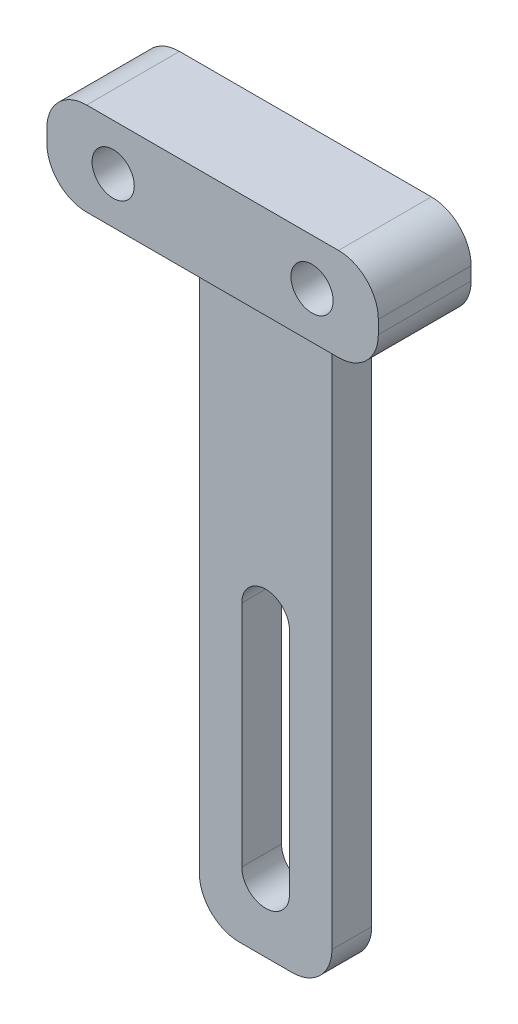
SolidWorks part; units mm, degrees
ref_plane "Front Plane" through (0, 0, 0) normal (0, 0, 1) x (1, 0, 0)
ref_plane "Top Plane" through (0, 0, 0) normal (0, 1, 0) x (1, 0, 0)
ref_plane "Right Plane" through (0, 0, 0) normal (1, 0, 0) x (0, 0, -1)
sketch "Sketch1" plane through (0, 0, 0) normal (0, 0, 1) x (1, 0, 0)
  line L0 (-12.5497, 17.2378) -> (-5.0497, 17.2378)
  line L1 (-30.0497, 24.2378) -> (-5.0497, 24.2378)
  line L2 (-30.0497, 24.2378) -> (-30.0497, 17.2378)
  line L3 (-30.0497, 17.2378) -> (-22.5497, 17.2378)
  line L4 (-5.0497, 24.2378) -> (-5.0497, 17.2378)
  line L5 (-30.0497, 24.2378) -> (-5.0497, 17.2378) construction
  line L6 (-30.0497, 17.2378) -> (-5.0497, 24.2378) construction
  line L7 (-17.5497, -23.6845) -> (-17.5497, -6.4384) construction
  line L8 (-19.3497, -23.6845) -> (-19.3497, -6.4384)
  line L9 (-22.5497, 17.2378) -> (-22.5497, -28.6845)
  line L10 (-22.5497, -28.6845) -> (-12.5497, -28.6845)
  line L11 (-12.5497, 17.2378) -> (-12.5497, -28.6845)
  line L12 (-15.7497, -23.6845) -> (-15.7497, -6.4384)
  arc A0 (-19.3497, -23.6845) -> (-15.7497, -23.6845) centre (-17.5497, -23.6845) ccw
  arc A1 (-15.7497, -6.4384) -> (-19.3497, -6.4384) centre (-17.5497, -6.4384) ccw
  point P0 (-17.5497, 20.7378)
  point P11 (-17.5497, -15.0614)
  dimension "D3" = 1.8
  dimension "D1" = 25
  dimension "D2" = 7
  dimension "D4" = 5
extrude "Boss-Extrude1" add sketch "Sketch1" along normal blind 3
sketch "Sketch3" plane through (0, 0, 3) normal (0, 0, 1) x (1, 0, 0)
  line L1 (-30.0497, 24.2378) -> (-5.0497, 24.2378)
  line L2 (-30.0497, 24.2378) -> (-30.0497, 17.2378)
  line L3 (-30.0497, 17.2378) -> (-5.0497, 17.2378)
  line L4 (-5.0497, 24.2378) -> (-5.0497, 17.2378)
extrude "Boss-Extrude2" add sketch "Sketch3" along normal blind 4 contours L3 L4 L1 L2
sketch "Sketch2" plane through (0, 0, 0) normal (0, 0, 1) x (1, 0, 0)
  line L0 (-17.5497, 24.2378) -> (-17.5497, -44.1864) construction
  line L2 (-5.0497, 24.2378) -> (-30.0497, 24.2378) construction
  circle A0 centre (-25.0497, 20.7378) radius 1.5923
  circle A1 centre (-10.0497, 20.7378) radius 1.5923
  dimension "D1" = 15
  dimension "D2" = 7.5
  dimension "D3" = 3.5
extrude "Cut-Extrude1" cut sketch "Sketch2" along normal blind 10
fillet "Fillet1" radius 3 9 edges at (-22.5497, -28.6845, 1.5) (-12.5497, -28.6845, 1.5) (-17.5497, 17.2378, 3) (-12.5497, 17.2378, 1.5) (-22.5497, 17.2378, 1.5) (-30.0497, 17.2378, 3.5) (-30.0497, 24.2378, 3.5) (-5.0497, 17.2378, 3.5) (-5.0497, 24.2378, 3.5)
